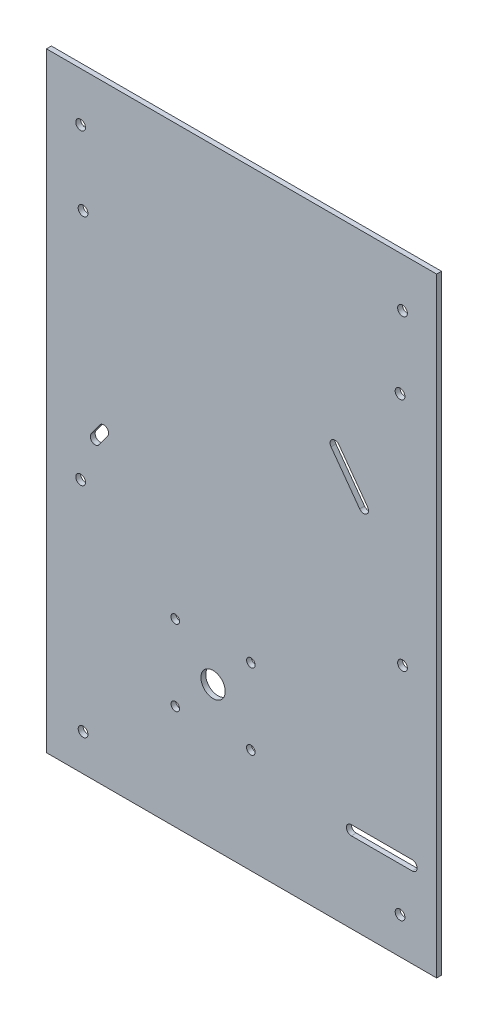
SolidWorks part; units mm, degrees
ref_plane "Front Plane" through (0, 0, 0) normal (0, 0, 1) x (1, 0, 0)
ref_plane "Top Plane" through (0, 0, 0) normal (0, 1, 0) x (1, 0, 0)
ref_plane "Right Plane" through (0, 0, 0) normal (1, 0, 0) x (0, 0, -1)
sketch "Sketch1" plane through (0, 0, 0) normal (0, 0, 1) x (1, 0, 0)
  line L1 (-80, 125) -> (80, 125)
  line L2 (-80, 125) -> (-80, -125)
  line L3 (-80, -125) -> (80, -125)
  line L4 (80, 125) -> (80, -125)
  line L5 (-80, 125) -> (80, -125) construction
  line L6 (-80, -125) -> (80, 125) construction
  point P0 (0, 0)
  dimension "D1" = 160
  dimension "D2" = 250
extrude "Boss-Extrude1" add sketch "Sketch1" against normal blind 2
sketch "Sketch2" plane through (0, 0, 0) normal (0, 0, 1) x (1, 0, 0)
  line L0 (70, -90) -> (45, -90) construction
  line L1 (70, -92) -> (45, -92)
  line L2 (70, -88) -> (45, -88)
  line L3 (80, -125) -> (80, 125) construction
  line L4 (-80, -125) -> (80, -125) construction
  line L5 (-80, 125) -> (-80, -125) construction
  line L6 (-56.52, 1.189) -> (-60.04, -3.67) construction
  line L7 (-54.9003, 0.0156) -> (-58.4203, -4.8433)
  line L8 (-58.1397, 2.3623) -> (-61.6597, -2.4967)
  line L9 (38.31, 43.18) -> (50.06, 26.9955) construction
  line L10 (39.9284, 44.355) -> (51.6784, 28.1705)
  line L11 (36.6916, 42.005) -> (48.4416, 25.8205)
  line L12 (80, 125) -> (-80, 125) construction
  arc A0 (70, -92) -> (70, -88) centre (70, -90) ccw
  arc A1 (45, -88) -> (45, -92) centre (45, -90) ccw
  circle A2 centre (-11.69, -66.6) radius 5
  arc A4 (-54.9003, 0.0156) -> (-58.1397, 2.3623) centre (-56.52, 1.189) ccw
  arc A5 (-61.6597, -2.4967) -> (-58.4203, -4.8433) centre (-60.04, -3.67) ccw
  arc A6 (39.9284, 44.355) -> (36.6916, 42.005) centre (38.31, 43.18) ccw
  arc A7 (48.4416, 25.8205) -> (51.6784, 28.1705) centre (50.06, 26.9955) ccw
  circle A8 centre (-66, -21) radius 2
  circle A9 centre (66, -21) radius 2
  circle A10 centre (-66, 105) radius 2
  circle A11 centre (66, 105) radius 2
  circle A12 centre (65, 75) radius 2
  circle A13 centre (-65, 75) radius 2
  circle A14 centre (-65, -110) radius 2
  circle A15 centre (65, -110) radius 2
  point P2 (57.5, -90)
  point P18 (-58.28, -1.2405)
  point P25 (44.185, 35.0878)
  dimension "D1" = 2
  dimension "D5" = 10
  dimension "D9" = 2
  dimension "D14" = 2
  dimension "D19" = 4
  dimension "D22" = 4
  dimension "D25" = 4
  dimension "D26" = 4
  dimension "D31" = 4
  dimension "D32" = 4
  dimension "D37" = 4
  dimension "D38" = 4
  dimension "D2" = 25
  dimension "D3" = 10
  dimension "D4" = 35
  dimension "D6" = 58.4
  dimension "D7" = 68.31
  dimension "D10" = 6
  dimension "D11" = 23.48
  dimension "D12" = 19.96
  dimension "D13" = 121.33
  dimension "D15" = 20
  dimension "D16" = 41.69
  dimension "D17" = 29.94
  dimension "D18" = 81.82
  dimension "D20" = 104
  dimension "D21" = 14
  dimension "D23" = 14
  dimension "D24" = 104
  dimension "D27" = 14
  dimension "D28" = 14
  dimension "D29" = 20
  dimension "D30" = 20
  dimension "D33" = 15
  dimension "D34" = 15
  dimension "D35" = 50
  dimension "D36" = 50
  dimension "D39" = 15
  dimension "D40" = 15
  dimension "D41" = 15
  dimension "D42" = 15
extrude "Cut-Extrude1" cut sketch "Sketch2" against normal through all
sketch "Sketch3" plane through (0, 0, 0) normal (0, 0, 1) x (1, 0, 0)
  circle A0 centre (-27.19, -51.1) radius 1.75
  circle A1 centre (3.81, -51.1) radius 1.75
  circle A2 centre (3.81, -82.1) radius 1.75
  circle A3 centre (-27.19, -82.1) radius 1.75
  circle A4 centre (-11.69, -66.6) radius 5 construction
  dimension "D1" = 3.5
  dimension "D2" = 3.5
  dimension "D3" = 3.5
  dimension "D4" = 3.5
  dimension "D10" = 15.5
  dimension "D5" = 15.5
  dimension "D6" = 15.5
  dimension "D7" = 15.5
  dimension "D8" = 15.5
  dimension "D9" = 15.5
  dimension "D11" = 15.5
  dimension "D12" = 15.5
extrude "Cut-Extrude2" cut sketch "Sketch3" against normal blind 10 contours A3 | A2 | A1 | A0
sketch "Sketch4" plane through (0, 0, 0) normal (0, 0, 1) x (1, 0, 0)
